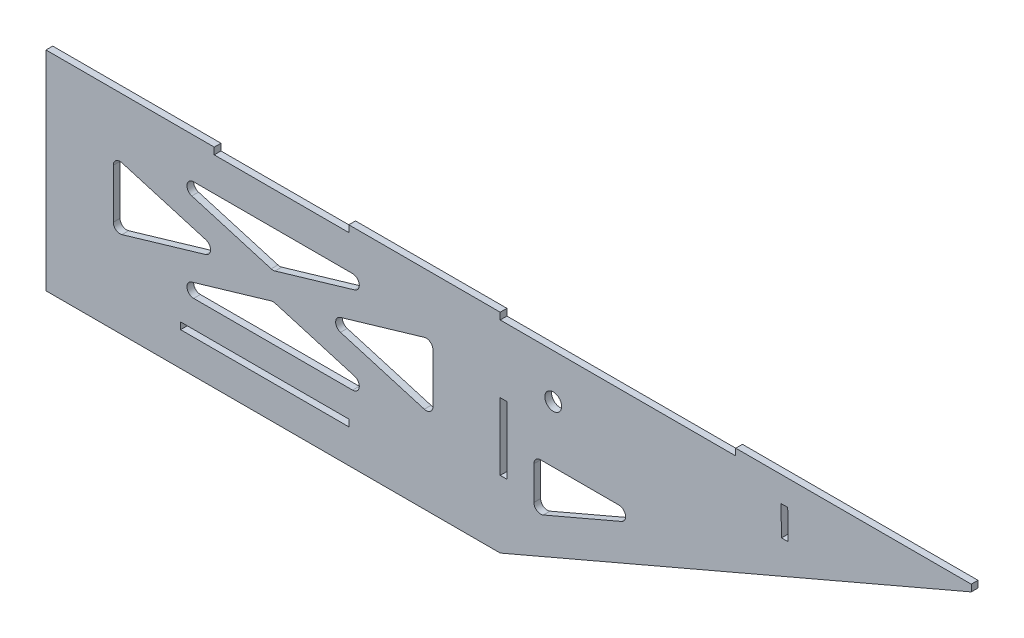
SolidWorks part; units mm, degrees
material "轻木"
ref_plane "前视基准面" through (0, 0, 0) normal (0, 0, 1) x (1, 0, 0)
ref_plane "上视基准面" through (0, 0, 0) normal (0, 1, 0) x (1, 0, 0)
ref_plane "右视基准面" through (0, 0, 0) normal (1, 0, 0) x (0, 0, -1)
sketch "草图1" plane through (0, 0, 0) normal (0, 0, 1) x (1, 0, 0)
  line L4 (0, 30) -> (0, -30)
  line L5 (0, 30) -> (135, 30)
  line L6 (0, -30) -> (135, -30)
  line L7 (135, 30) -> (135, -30)
  line L8 (135, 30) -> (275, 30)
  line L9 (275, 30) -> (135, -30)
  line L10 (150.7605, 16.8689) -> (218.5554, 18.0523)
  line L11 (218.5554, 18.0523) -> (218.4434, 24.4703)
  line L12 (147.7878, -13.8052) -> (171.044, -3.8383)
  line L13 (145, -2) -> (145, -11.9669)
  line L14 (147, 0) -> (170.2562, 0)
  line L15 (218.5554, 18.0523) -> (218.5966, 15.6927)
  line L16 (40, -18) -> (40, -20)
  line L17 (40, -18) -> (90, -18)
  line L18 (40, -20) -> (90, -20)
  line L19 (90, -18) -> (90, -20)
  line L20 (20, 12.3271) -> (20, -2.3271)
  line L21 (43.888, 20) -> (91.112, 20)
  line L22 (43.888, -10) -> (91.112, -10)
  line L23 (115, 12.3271) -> (115, -2.3271)
  line L24 (87.5237, 3.0813) -> (112.4357, -4.2458)
  line L25 (47.4763, 3.0813) -> (22.5643, -4.2458)
  line L26 (22.5643, 14.2458) -> (47.4763, 6.9187)
  line L27 (87.5237, 6.9187) -> (112.4357, 14.2458)
  line L28 (43.3237, 16.0813) -> (66.9357, 9.1366)
  line L29 (91.6763, 16.0813) -> (68.0643, 9.1366)
  line L30 (43.3237, -6.0813) -> (66.9357, 0.8634)
  line L31 (91.6763, -6.0813) -> (68.0643, 0.8634)
  line L32 (135, 10) -> (135, -10)
  line L33 (135, 10) -> (137, 10)
  line L34 (135, -10) -> (137, -10)
  line L35 (137, 10) -> (137, -10)
  line L36 (0, 32) -> (0, 30)
  line L37 (0, 32) -> (50, 32)
  line L38 (0, 30) -> (50, 30)
  line L39 (50, 32) -> (50, 30)
  line L40 (90, 32) -> (90, 30)
  line L41 (90, 32) -> (135, 32)
  line L42 (90, 30) -> (135, 30)
  line L43 (135, 32) -> (135, 30)
  line L44 (205, 32) -> (205, 30)
  line L45 (205, 32) -> (275, 32)
  line L46 (205, 30) -> (275, 30)
  line L47 (275, 32) -> (275, 30)
  line L48 (218.4434, 24.4703) -> (220.4431, 24.5052)
  line L49 (220.4431, 24.5052) -> (220.5963, 15.7276)
  line L50 (220.5963, 15.7276) -> (218.5966, 15.6927)
  arc A0 (147, 0) -> (145, -2) centre (147, -2) ccw
  arc A1 (171.044, -3.8383) -> (170.2562, 0) centre (170.2562, -2) ccw
  arc A2 (147.7878, -13.8052) -> (145, -11.9669) centre (147, -11.9669) cw
  circle A3 centre (150.7605, 16.8689) radius 2.5
  arc A5 (22.5643, 14.2458) -> (20, 12.3271) centre (22, 12.3271) ccw
  arc A6 (47.4763, 6.9187) -> (47.4763, 3.0813) centre (46.912, 5) cw
  arc A7 (22.5643, -4.2458) -> (20, -2.3271) centre (22, -2.3271) cw
  arc A8 (112.4357, -4.2458) -> (115, -2.3271) centre (113, -2.3271) ccw
  arc A9 (115, 12.3271) -> (112.4357, 14.2458) centre (113, 12.3271) ccw
  arc A10 (87.5237, 3.0813) -> (87.5237, 6.9187) centre (88.088, 5) cw
  arc A11 (43.3237, 16.0813) -> (43.888, 20) centre (43.888, 18) cw
  arc A12 (91.112, 20) -> (91.6763, 16.0813) centre (91.112, 18) cw
  arc A13 (66.9357, 9.1366) -> (68.0643, 9.1366) centre (67.5, 11.0553) ccw
  arc A14 (43.888, -10) -> (43.3237, -6.0813) centre (43.888, -8) cw
  arc A15 (91.6763, -6.0813) -> (91.112, -10) centre (91.112, -8) cw
  arc A16 (68.0643, 0.8634) -> (66.9357, 0.8634) centre (67.5, -1.0553) ccw
  point P0 (275, 30)
  point P7 (145, -15)
  point P8 (145, 0)
  point P14 (145, 0)
  point P20 (145, -15)
  point P32 (30, 20)
  point P37 (105, 20)
  point P38 (20, 15)
  point P39 (20, -5)
  point P40 (115, 15)
  point P41 (115, -5)
  point P42 (105, -10)
  point P47 (30, -10)
  point P80 (0, 32)
  point P81 (50, 32)
  point P82 (90, 32)
  point P83 (135, 32)
  point P84 (205, 32)
  point P85 (275, 32)
  dimension "D1" = 2
  dimension "D2" = 2
  dimension "D3" = 2
  dimension "D6" = 2
  dimension "D7" = 2
  dimension "D8" = 2
  dimension "D9" = 2
  dimension "D10" = 2
  dimension "D11" = 2
  dimension "D12" = 2
  dimension "D13" = 2
  dimension "D14" = 2
  dimension "D15" = 2
  dimension "D16" = 2
  dimension "D17" = 2
extrude "凸台-拉伸1" add sketch "草图1" along normal blind 2
